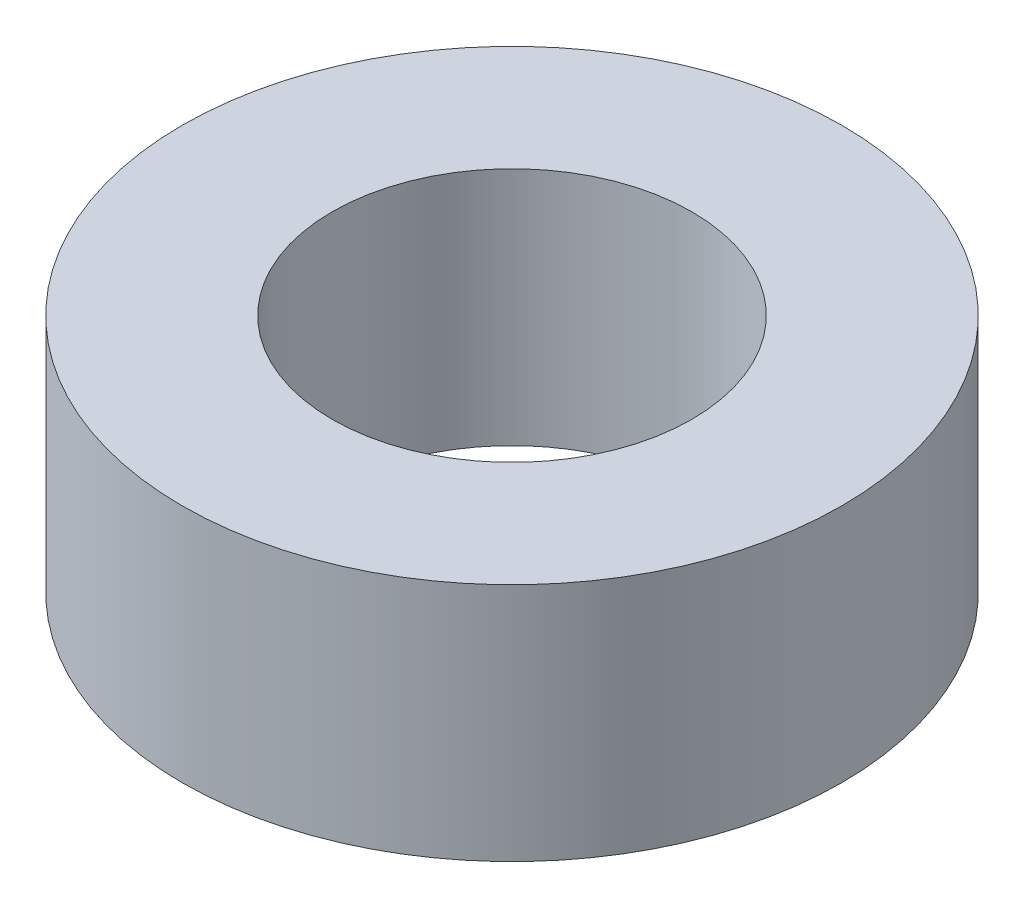
SolidWorks part; units mm, degrees
ref_plane "Front Plane" through (0, 0, 0) normal (0, 0, 1) x (1, 0, 0)
ref_plane "Top Plane" through (0, 0, 0) normal (0, 1, 0) x (1, 0, 0)
ref_plane "Right Plane" through (0, 0, 0) normal (1, 0, 0) x (0, 0, -1)
sketch "Sketch2" plane through (0, 0, 0) normal (0, 1, 0) x (1, 0, 0)
  circle A0 centre (0, 0) radius 5.5
  circle A1 centre (0, 0) radius 3
  dimension "D1" = 11
  dimension "D2" = 6
extrude "Boss-Extrude1" add sketch "Sketch2" along normal blind 4
